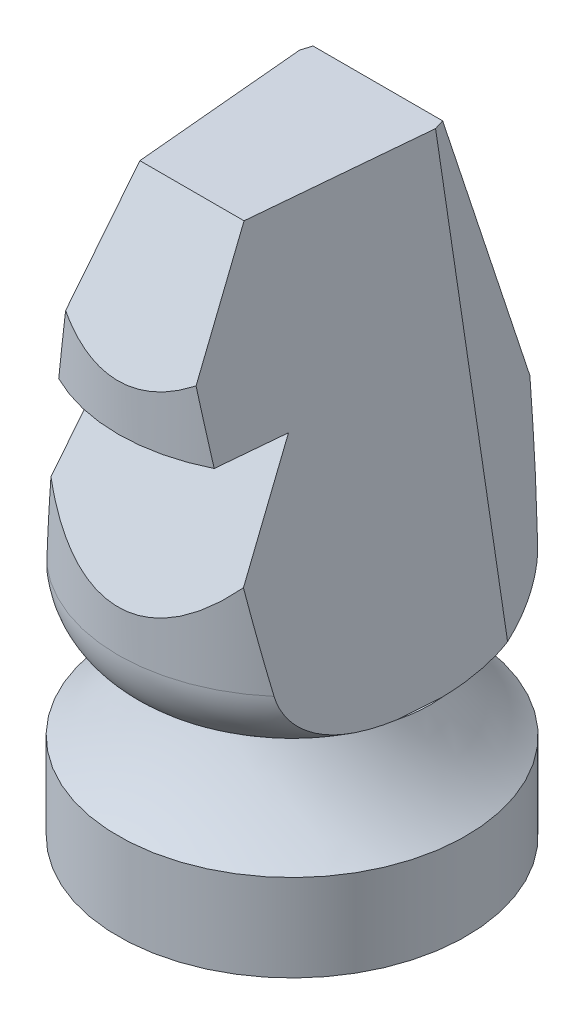
SolidWorks part; units mm, degrees
ref_plane "Front Plane" through (0, 0, 0) normal (0, 0, 1) x (1, 0, 0)
ref_plane "Top Plane" through (0, 0, 0) normal (0, 1, 0) x (1, 0, 0)
ref_plane "Right Plane" through (0, 0, 0) normal (1, 0, 0) x (0, 0, -1)
sketch "Sketch1" plane through (0, 0, 0) normal (1, 0, 0) x (0, 0, -1)
  line L1 (-20, -10) -> (-20, -20)
  line L2 (-20, -20) -> (0, -20)
  line L3 (0, -20) -> (0, 0) construction
  line L4 (0, 0) -> (0, -20)
  line L7 (0, 0) -> (0, 50)
  line L8 (0, 50) -> (-20, 50)
  line L9 (-20, 8) -> (-20, 50)
  arc A0 (-12, 0) -> (-20, -10) centre (-34.8705, 10.0964) cw
  arc A1 (-12, 0) -> (-20, 8) centre (-12, 8) cw
  dimension "D4" = 25
  dimension "D6" = 8
  dimension "D1" = 20
  dimension "D2" = 70
  dimension "D3" = 10
  dimension "D5" = 12
  dimension "D7" = 20
revolve "Revolve1" add sketch "Sketch1" angle 360 about L3
sketch "Sketch3" plane through (0, 50, 0) normal (0, 1, 0) x (1, 0, 0)
  line L0 (0, -20) -> (0, 20)
  circle A0 centre (0, 0) radius 20 construction
ref_plane "Plane1" through (-8.5505, 48.4923, 0) normal (0.1736, -0.9848, 0) x (0, 0, -1)
sketch "Sketch4" plane through (-8.5505, 48.4923, 0) normal (0.1736, -0.9848, 0) x (0, 0, -1)
  line L0 (-25, 13.3786) -> (8.6783, 16.3786)
  line L1 (8.6783, 16.3786) -> (25, 11.3786)
  line L2 (25, 11.3786) -> (25, 28.3786)
  line L3 (25, 28.3786) -> (-25, 28.3786)
  line L4 (-25, 28.3786) -> (-25, 13.3786)
  line L5 (-20, 8.6824) -> (20, 8.6824) construction
  ellipse E1 centre (0, 8.6824) end of major axis (-20, 8.6824) minor radius 19.6962 construction
  ellipse E2 centre (0, 8.6824) end of major axis (-20, 8.6824) minor radius 19.6962
  dimension "D1" = 12
  dimension "D2" = 15
  dimension "D3" = 17
  dimension "D4" = 50
  dimension "D6" = 7.6962
extrude "Cut-Extrude1" cut sketch "Sketch4" along normal blind 51 contours L1 E2 L0
mirror "Mirror1" about plane through (0, 0, 0) normal (1, 0, 0) of "Cut-Extrude1"
sketch "Sketch5" plane through (0, 0, 0) normal (1, 0, 0) x (0, 0, -1)
  line L0 (-24.0563, 5.7611) -> (-10.062, 30)
  line L1 (-10.062, 30) -> (-23.062, 30)
  line L2 (-23.062, 30) -> (-1.7, 67)
  line L3 (-1.7, 67) -> (5.3, 67)
  line L4 (5.3, 67) -> (20.2431, 11.2315)
  line L5 (-20, 50) -> (20, 50) construction
  line L6 (-24.0563, 5.7611) -> (-55.6498, 36.4673)
  line L7 (-55.6498, 36.4673) -> (-11.1105, 82.2936)
  line L8 (-11.1105, 82.2936) -> (36.2237, 75.286)
  line L9 (36.2237, 75.286) -> (20.2431, 11.2315)
  dimension "D1" = 20
  dimension "D2" = 60
  dimension "D3" = 13
  dimension "D4" = 60
  dimension "D5" = 120
  dimension "D6" = 105
  dimension "D7" = 7
  dimension "D8" = 37
extrude "Cut-Extrude2" cut sketch "Sketch5" against normal through all both and the other way through all
scale "缩放比例1" scale about origin uniform scaling yes scale factor 0.6
